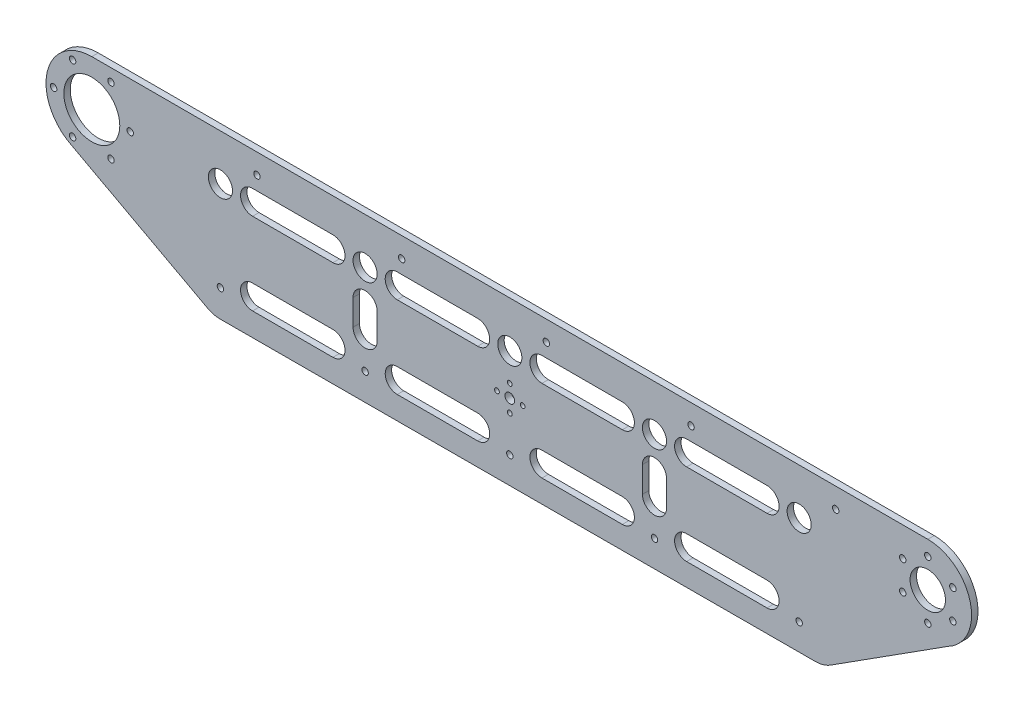
SolidWorks part; units mm, degrees
material "3.1305 (EN-AW 2117)"
ref_plane "Alzado" through (0, 0, 0) normal (0, 0, 1) x (1, 0, 0)
ref_plane "Planta" through (0, 0, 0) normal (0, 1, 0) x (1, 0, 0)
ref_plane "Vista lateral" through (0, 0, 0) normal (1, 0, 0) x (0, 0, -1)
sketch "Croquis1" plane through (0, 0, 0) normal (0, 0, 1) x (1, 0, 0)
  line L4 (102.5, 23.182) -> (90, 21.1607) construction
  line L5 (90, -23.8925) -> (180, -23.8925) construction
  line L6 (-102.5, -9.9669) -> (-83.0991, -6.8298) construction
  line L7 (-215.9366, -23.8925) -> (-260, -23.8925) construction
  line L8 (-90, -23.8925) -> (-92, -23.8925) construction
  line L9 (-188.6184, -23.8925) -> (-182, -23.8925) construction
  line L10 (-260, -23.8925) -> (-260, 1.2874) construction
  line L11 (-178.8951, -40.8565) -> (179.1956, -40.2202)
  line L12 (-260, 32.1075) -> (-180, -23.8925) construction
  line L18 (179.1956, -40.2202) -> (190.0108, -40.2202)
  line L19 (0, -23.8925) -> (-12.5, -23.8925) construction
  line L20 (-180, -23.8925) -> (-167.5, -23.8925) construction
  line L21 (-90, -23.8925) -> (-92, -23.8925) construction
  line L24 (-90, -23.8925) -> (-90, 32.1075) construction
  line L28 (-182, -23.9062) -> (-188.6184, -23.8925) construction
  line L30 (-180, -23.8925) -> (-196.3846, -12.4232) construction
  line L31 (-196.3846, -12.4232) -> (-221.6689, 5.2758) construction
  line L32 (-260, 32.1075) -> (-243.6154, 20.6383) construction
  line L36 (-273.3321, 6.9181) -> (-188.3167, -38.7192)
  line L41 (-90, 32.1075) -> (-90, 12.1075) construction
  line L42 (-90, -23.8925) -> (-90, -3.8925) construction
  line L43 (-82.5, 12.1075) -> (-82.5, -3.8925)
  line L44 (-97.5, 12.1075) -> (-97.5, -3.8925)
  line L45 (-90, 44.6075) -> (-90, -11.3925) construction
  line L46 (-20, 24.6075) -> (-70, 24.6075)
  line L47 (-20, 39.6075) -> (-70, 39.6075)
  line L48 (287.24, 32.1075) -> (284.0739, 32.1075) construction
  line L50 (260, 60.6075) -> (260, 33.3675) construction
  line L51 (90, 44.6075) -> (90, -11.3925) construction
  line L52 (90, -23.8925) -> (90, -3.8925) construction
  line L53 (90, 32.1075) -> (90, 12.1075) construction
  line L54 (260, 33.3675) -> (260, 40.3675) construction
  line L55 (160, -26.3925) -> (110, -26.3925)
  line L56 (-260, 4.1) -> (-260, 32.1075) construction
  line L57 (160, -11.3925) -> (110, -11.3925)
  line L58 (20, -11.3925) -> (70, -11.3925)
  line L59 (20, 39.6075) -> (70, 39.6075)
  line L60 (260, 33.3675) -> (260, 26.3675) construction
  line L65 (-160, 39.6075) -> (-110, 39.6075)
  line L66 (-160, 24.6075) -> (-110, 24.6075)
  line L67 (20, -26.3925) -> (70, -26.3925)
  line L83 (-260, 60.6075) -> (260, 60.6075)
  line L87 (-288.5, 32.1075) -> (-284.0739, 32.1075) construction
  line L88 (-20, -26.3925) -> (-70, -26.3925)
  line L89 (160, 24.6075) -> (110, 24.6075)
  line L90 (-20, -11.3925) -> (-70, -11.3925)
  line L91 (-167.5, -23.8925) -> (-180, -23.8925) construction
  line L92 (-102.5, 23.182) -> (-90, 21.1607) construction
  line L93 (160, 39.6075) -> (110, 39.6075)
  line L94 (-6.5, 6.6075) -> (-141.7981, 6.6075) construction
  line L95 (90, -23.8925) -> (88, -23.8925) construction
  line L96 (-135, 39.6075) -> (-135, 14.7545) construction
  line L97 (135, 39.6075) -> (135, 20.6383) construction
  line L98 (-88, -23.8925) -> (-90, -23.8925) construction
  line L99 (-160, -26.3925) -> (-110, -26.3925)
  line L100 (-83.0991, -6.8298) -> (-102.5, -9.9669) construction
  line L101 (-90, 21.1607) -> (-102.5, 23.182) construction
  line L102 (-160, -11.3925) -> (-110, -11.3925)
  line L103 (83.0991, -6.8298) -> (102.5, -9.9669) construction
  line L106 (90, 21.1607) -> (102.5, 23.182) construction
  line L115 (90, -23.8925) -> (90, 32.1075) construction
  line L116 (90, -23.8925) -> (92, -23.8925) construction
  line L119 (265.4417, 4.633) -> (265.4184, 5.0492) construction
  line L121 (90, -23.8925) -> (92, -23.8925) construction
  line L122 (102.5, -9.9669) -> (83.0991, -6.8298) construction
  line L124 (20, 24.6075) -> (70, 24.6075)
  line L125 (97.5, 12.1075) -> (97.5, -3.8925)
  line L126 (82.5, 12.1075) -> (82.5, -3.8925)
  line L127 (272.7427, 9.2918) -> (199.4836, -37.4553)
  circle A5 centre (0, -23.8925) radius 2
  circle A6 centre (-90, -23.8925) radius 2
  circle A7 centre (-180, -23.8925) radius 2
  circle A25 centre (-90, 32.1075) radius 7.5
  arc A26 (-82.5, 12.1075) -> (-97.5, 12.1075) centre (-90, 12.1075) ccw
  arc A27 (-97.5, -3.8925) -> (-82.5, -3.8925) centre (-90, -3.8925) ccw
  arc A28 (-20, 39.6075) -> (-20, 24.6075) centre (-20, 32.1075) cw
  arc A29 (-70, 24.6075) -> (-70, 39.6075) centre (-70, 32.1075) cw
  circle A30 centre (0, 32.1075) radius 7.5
  circle A51 centre (-260, 32.1075) radius 17.4
  arc A52 (-260, 60.6075) -> (-273.3321, 6.9181) centre (-260, 32.1075) ccw
  arc A54 (-188.3167, -38.7192) -> (-178.8951, -40.8565) centre (-180, -23.8925) ccw
  arc A56 (260, 60.6075) -> (272.7427, 9.2918) centre (260, 33.3675) cw
  circle A57 centre (260, 33.3675) radius 11
  arc A58 (70, 24.6075) -> (70, 39.6075) centre (70, 32.1075) ccw
  arc A59 (20, 39.6075) -> (20, 24.6075) centre (20, 32.1075) ccw
  arc A60 (97.5, -3.8925) -> (82.5, -3.8925) centre (90, -3.8925) cw
  arc A61 (82.5, 12.1075) -> (97.5, 12.1075) centre (90, 12.1075) cw
  circle A62 centre (90, 32.1075) radius 7.5
  circle A66 centre (90, -23.8925) radius 2
  arc A71 (-160, 39.6075) -> (-160, 24.6075) centre (-160, 32.1075) ccw
  arc A72 (-110, 24.6075) -> (-110, 39.6075) centre (-110, 32.1075) ccw
  arc A73 (160, 39.6075) -> (160, 24.6075) centre (160, 32.1075) cw
  arc A74 (110, 24.6075) -> (110, 39.6075) centre (110, 32.1075) cw
  circle A75 centre (-180, 32.1075) radius 7.5
  circle A76 centre (180, 32.1075) radius 7.5
  circle A77 centre (-8, 6.6075) radius 1.5
  circle A78 centre (0, 14.6075) radius 1.5
  circle A79 centre (8, 6.6075) radius 1.5
  circle A80 centre (0, -1.3925) radius 1.5
  circle A81 centre (0, 6.6075) radius 3
  circle A82 centre (180, -23.8925) radius 2
  arc A83 (199.4836, -37.4553) -> (190.0108, -40.2202) centre (190.0108, -22.6102) cw
  arc A84 (160, -26.3925) -> (160, -11.3925) centre (160, -18.8925) ccw
  arc A85 (110, -11.3925) -> (110, -26.3925) centre (110, -18.8925) ccw
  arc A86 (20, -26.3925) -> (20, -11.3925) centre (20, -18.8925) cw
  arc A87 (70, -11.3925) -> (70, -26.3925) centre (70, -18.8925) cw
  arc A88 (-20, -26.3925) -> (-20, -11.3925) centre (-20, -18.8925) ccw
  arc A89 (-70, -11.3925) -> (-70, -26.3925) centre (-70, -18.8925) ccw
  arc A90 (-110, -11.3925) -> (-110, -26.3925) centre (-110, -18.8925) cw
  arc A91 (-160, -26.3925) -> (-160, -11.3925) centre (-160, -18.8925) cw
  point P0 (0, 6.6075)
  dimension "D5" = 4
  dimension "D7" = 4
  dimension "D9" = 4
  dimension "D11" = 22
  dimension "D10" = 57
  dimension "D12" = 27.24
  dimension "D15" = 7
  dimension "D16" = 7
  dimension "D18" = 4
  dimension "D20" = 6
  dimension "D21" = 34.8
  dimension "D23" = 4
  dimension "D24" = 90
  dimension "D25" = 15
  dimension "D28" = 15
  dimension "D30" = 15
  dimension "D31" = 15
  dimension "D33" = 17.61
  dimension "D17" = 3
  dimension "D32" = 4
  dimension "D4" = 30.5
  dimension "D6" = 90
  dimension "D8" = 90
  dimension "D13" = 80
  dimension "D14" = 56
  dimension "D19" = 20
  dimension "D22" = 20
  dimension "D26" = 20
  dimension "D27" = 56
  dimension "D29" = 20
extrude "Saliente-Extruir1" add sketch "Croquis1" along normal mid plane 4
sketch "Croquis2" plane through (0, 0, 2) normal (0, 0, 1) x (1, 0, 0)
  line L0 (-285.74, 32.1075) -> (-283.74, 32.1075) construction
  line L1 (-260, 32.1075) -> (-271.95, 52.8055) construction
  line L2 (-260, 32.1075) -> (-248.05, 52.8055) construction
  line L3 (-260, 32.1075) -> (-271.95, 11.4095) construction
  line L4 (-260, 32.1075) -> (-248.05, 11.4095) construction
  line L5 (-260, 32.1075) -> (-236.1, 32.1075) construction
  line L6 (-260, 32.1075) -> (-283.74, 32.1075) construction
  circle A1 centre (-283.74, 32.1075) radius 2
  circle A3 centre (-271.95, 52.8055) radius 2
  circle A4 centre (-248.05, 52.8055) radius 2
  circle A5 centre (-236.1, 32.1075) radius 2
  circle A6 centre (-248.05, 11.4095) radius 2
  circle A7 centre (-271.95, 11.4095) radius 2
  dimension "D2" = 4
  dimension "D12" = 4
  dimension "D13" = 4
  dimension "D14" = 4
  dimension "D15" = 4
  dimension "D16" = 4
  dimension "D3" = 60
  dimension "D4" = 60
  dimension "D5" = 60
  dimension "D6" = 60
  dimension "D7" = 23.9
  dimension "D8" = 23.9
  dimension "D9" = 23.9
  dimension "D10" = 23.9
  dimension "D11" = 23.9
extrude "Cortar-Extruir1" cut sketch "Croquis2" against normal blind 10
sketch "Croquis3" plane through (0, 0, 2) normal (0, 0, 1) x (1, 0, 0)
  line L0 (260, 33.3675) -> (260, 51.3675) construction
  circle A0 centre (260, 51.3675) radius 2
  circle A6 centre (275.5885, 42.3675) radius 2
  circle A7 centre (275.5885, 24.3675) radius 2
  circle A8 centre (260, 15.3675) radius 2
  circle A9 centre (244.4115, 24.3675) radius 2
  circle A10 centre (244.4115, 42.3675) radius 2
  dimension "D2" = 4
  dimension "D1" = 18
  dimension "D3" = 6
extrude "Cortar-Extruir2" cut sketch "Croquis3" against normal blind 10
sketch "Croquis4" plane through (0, 0, 2) normal (0, 0, 1) x (1, 0, 0)
  line L1 (-157.2568, 46.1075) -> (-157.2568, 48.1075) construction
  line L2 (-157.2568, 48.1075) -> (-67.2568, 48.1075) construction
  line L3 (-67.2568, 48.1075) -> (22.7432, 48.1075) construction
  line L4 (22.7432, 48.1075) -> (112.7432, 48.1075) construction
  line L5 (112.7432, 48.1075) -> (202.7432, 48.1075) construction
  line L6 (204.7432, 48.1075) -> (202.7432, 48.1075) construction
  circle A0 centre (-157.2568, 48.1075) radius 2
  circle A1 centre (-67.2568, 48.1075) radius 2
  circle A2 centre (22.7432, 48.1075) radius 2
  circle A3 centre (112.7432, 48.1075) radius 2
  circle A4 centre (202.7432, 48.1075) radius 2
  dimension "D3" = 4
  dimension "D8" = 4
  dimension "D9" = 4
  dimension "D10" = 4
  dimension "D11" = 4
  dimension "D4" = 90
  dimension "D5" = 90
  dimension "D6" = 90
  dimension "D7" = 90
extrude "Cortar-Extruir3" cut sketch "Croquis4" against normal blind 10
